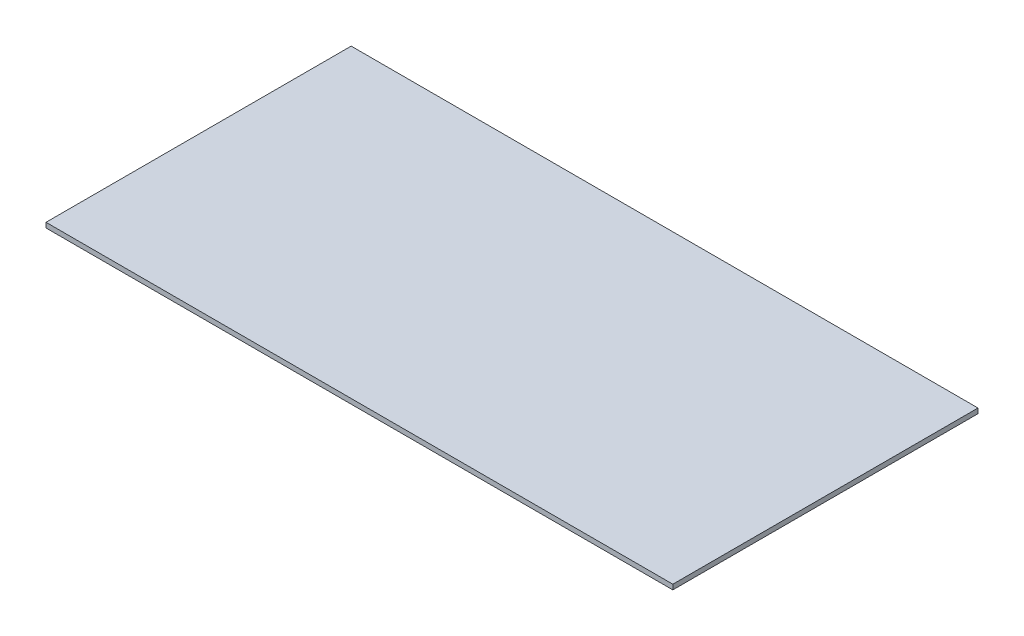
SolidWorks part; units mm, degrees
material "PBT General Purpose"
ref_plane "Front Plane" through (0, 0, 0) normal (0, 0, 1) x (1, 0, 0)
ref_plane "Top Plane" through (0, 0, 0) normal (0, 1, 0) x (1, 0, 0)
ref_plane "Right Plane" through (0, 0, 0) normal (1, 0, 0) x (0, 0, -1)
sketch "Sketch1" plane through (0, 0, 0) normal (0, 1, 0) x (1, 0, 0)
  line L1 (0, 0) -> (190, 0)
  line L2 (0, 0) -> (0, 92.5)
  line L3 (0, 92.5) -> (190, 92.5)
  line L4 (190, 0) -> (190, 92.5)
  dimension "D1" = 190
  dimension "D2" = 92.5
extrude "Boss-Extrude1" add sketch "Sketch1" along normal blind 1.5
